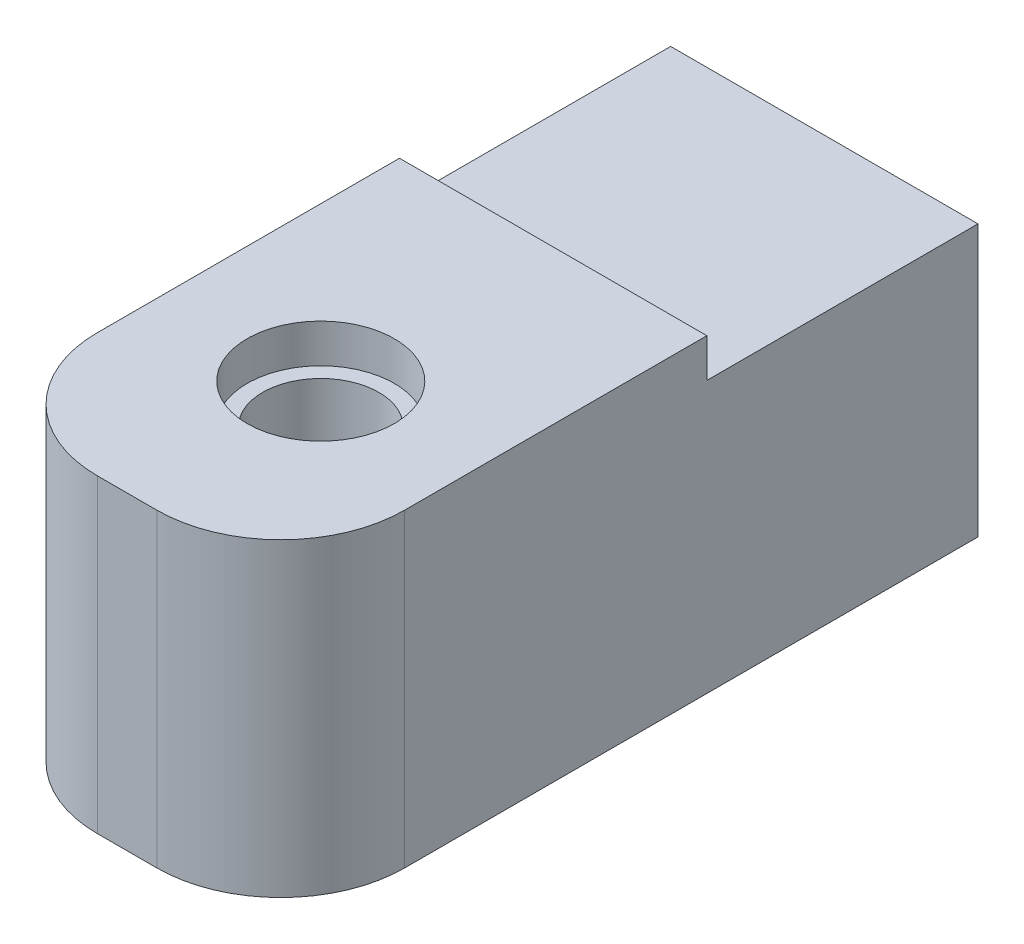
SolidWorks part; units mm, degrees
material "Plain Carbon Steel"
ref_plane "Front Plane" through (0, 0, 0) normal (0, 0, 1) x (1, 0, 0)
ref_plane "Top Plane" through (0, 0, 0) normal (0, 1, 0) x (1, 0, 0)
ref_plane "Right Plane" through (0, 0, 0) normal (1, 0, 0) x (0, 0, -1)
sketch "Sketch1" plane through (0, 0, 0) normal (0, 0, 1) x (1, 0, 0)
  line L1 (-29.4598, 9.2127) -> (-4.268, 9.2127)
  line L2 (-29.4598, 9.2127) -> (-29.4598, -16.1873)
  line L3 (-29.4598, -16.1873) -> (-4.268, -16.1873)
  line L4 (-4.268, 9.2127) -> (-4.268, -16.1873)
  line L5 (-29.4598, 9.2127) -> (-4.268, -16.1873) construction
  line L6 (-29.4598, -16.1873) -> (-4.268, 9.2127) construction
  point P0 (-16.8639, -3.4873)
  dimension "D1" = 25.4
extrude "Boss-Extrude1" add sketch "Sketch1" along normal blind 57.15
sketch "Sketch2" plane through (0, 0, 0) normal (0, 0, -1) x (-1, 0, 0)
  circle A1 centre (16.8989, -3.4524) radius 4.6967
extrude "Cut-Extrude1" cut sketch "Sketch2" against normal blind 30.1752
sketch "Sketch3" plane through (-4.268, 0, 0) normal (1, 0, 0) x (0, 0, -1)
  line L1 (0, 9.2127) -> (-22.225, 9.2127)
  line L2 (0, 9.2127) -> (0, 6.0377)
  line L3 (0, 6.0377) -> (-22.225, 6.0377)
  line L4 (-22.225, 9.2127) -> (-22.225, 6.0377)
  dimension "D1" = 22.225
  dimension "D2" = 3.175
extrude "Cut-Extrude2" cut sketch "Sketch3" against normal blind 30.1752
sketch "Sketch11" plane through (0, 9.2127, 0) normal (0, 1, 0) x (1, 0, 0)
  line L0 (-4.268, -57.15) -> (-29.4598, -57.15) construction
  circle A0 centre (-16.8639, -41.275) radius 6.0325
  dimension "D1" = 15.875
  dimension "D2" = 12.065
extrude "Cut-Extrude5" cut sketch "Sketch11" against normal blind 3.175
sketch "Sketch12" plane through (0, 6.0377, 0) normal (0, 1, 0) x (1, 0, 0)
  circle A0 centre (-16.8639, -41.275) radius 4.7625
  dimension "D1" = 9.525
extrude "Cut-Extrude6" cut sketch "Sketch12" against normal through all
fillet "Fillet1" radius 10.16 1 edges at (-4.268, -3.4873, 57.15)
fillet "Fillet2" radius 10.16 1 edges at (-29.4598, -3.4873, 57.15)
